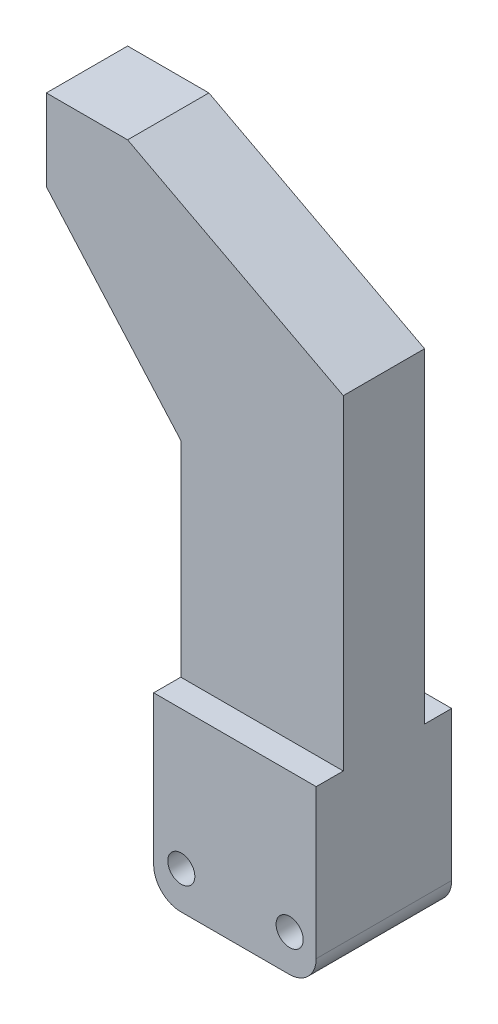
SolidWorks part; units mm, degrees
ref_plane "前视基准面" through (0, 0, 0) normal (0, 0, 1) x (1, 0, 0)
ref_plane "上视基准面" through (0, 0, 0) normal (0, 1, 0) x (1, 0, 0)
ref_plane "右视基准面" through (0, 0, 0) normal (1, 0, 0) x (0, 0, -1)
sketch "草图1" plane through (0, 0, 0) normal (0, 0, 1) x (1, 0, 0)
  line L0 (0, 0) -> (0, 72)
  line L1 (0, 72) -> (-47.77, 97.1798)
  line L2 (-47.77, 97.1798) -> (-65.77, 97.1798)
  line L3 (-65.77, 97.1798) -> (-65.77, 79.1798)
  line L4 (-65.77, 79.1798) -> (-36, 45.4345)
  line L5 (-36, 45.4345) -> (-36, 0)
  line L6 (-36, 0) -> (0, 0)
  dimension "D1" = 72
  dimension "D2" = 54
  dimension "D3" = 18
  dimension "D4" = 18
  dimension "D5" = 45
  dimension "D6" = 36
extrude "凸台-拉伸1" add sketch "草图1" along normal mid plane 18
sketch "草图2" plane through (0, 0, 0) normal (1, 0, 0) x (0, 0, -1)
  line L0 (-3.6, 0) -> (-8.9778, -6)
  line L1 (-9, 0) -> (9, 0) construction
  line L2 (-8.9778, -6) -> (9.0222, -6)
  line L3 (9.0222, -6) -> (3.6, 0)
  line L4 (-3.6, 0) -> (3.6, 0)
  point P7 (-3.6, 0)
  point P8 (3.6, 0)
  dimension "D1" = 5.4
  dimension "D2" = 5.4
  dimension "D3" = 18
  dimension "D4" = 6
extrude "凸台-拉伸2" add sketch "草图2" against normal blind 36 contours L4 L3 L2 L0
sketch "草图3" plane through (0, 0, 0) normal (0, 0, 1) x (1, 0, 0)
  line L1 (-36, 0) -> (0, 0)
  line L2 (-36, 0) -> (-36, -39)
  line L3 (-36, -39) -> (0, -39)
  line L4 (0, 0) -> (0, -39)
  dimension "D1" = 36
  dimension "D2" = 39
extrude "凸台-拉伸4" add sketch "草图3" along normal mid plane 30
sketch "草图4" plane through (0, 0, 0) normal (1, 0, 0) x (0, 0, -1)
  line L0 (0, 0) -> (0, -39) construction
  line L1 (-15, -39) -> (15, -39) construction
  line L2 (-9, 0) -> (-3.6, 0)
  line L3 (-3.6, 0) -> (-9, -6)
  line L4 (-9, -6) -> (9, -6)
  line L5 (-15, 0) -> (-15, -39) construction
  line L6 (3.6, 0) -> (9, -6)
  line L7 (3.6, 0) -> (9, 0)
  point P13 (0, -6)
  dimension "D1" = 3.6
  dimension "D2" = 6
  dimension "D3" = 9
sketch "草图5" plane through (0, 0, 15) normal (0, 0, 1) x (1, 0, 0)
  circle A0 centre (-29.8813, -30.6738) radius 3
  circle A1 centre (-5.8818, -30.824) radius 3
  dimension "D1" = 6
  dimension "D2" = 6
  dimension "D3" = 24
extrude "切除-拉伸1" cut sketch "草图5" against normal through all contours A1 | A0
fillet "圆角1" radius 6 2 edges at (-36, -39, 0) (0, -39, 0)
